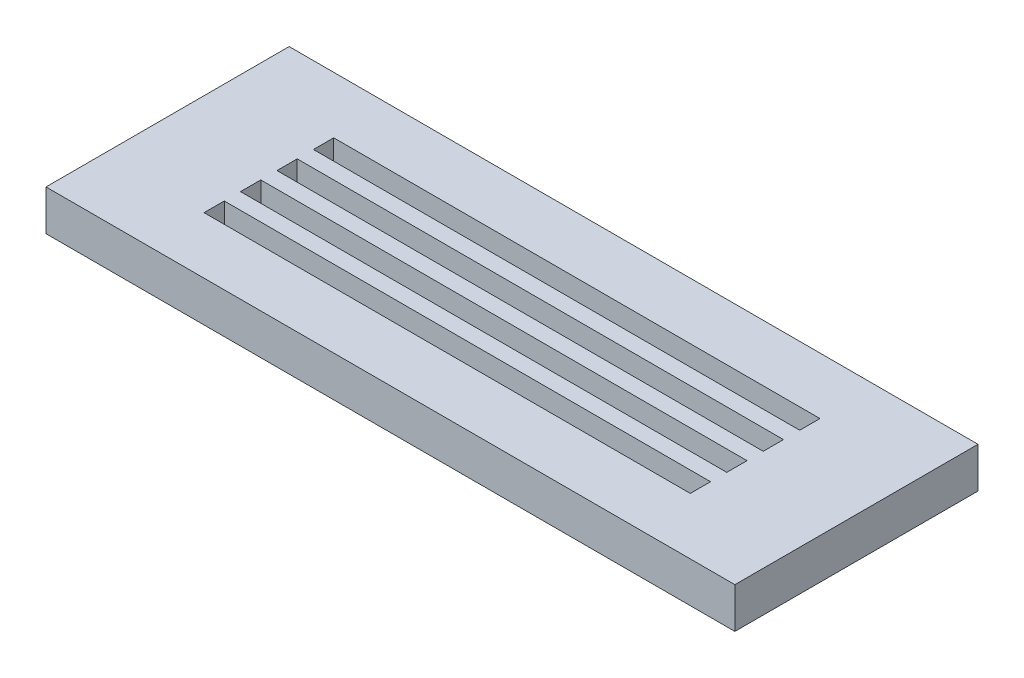
SolidWorks part; units mm, degrees
ref_plane "前视基准面" through (0, 0, 0) normal (0, 0, 1) x (1, 0, 0)
ref_plane "上视基准面" through (0, 0, 0) normal (0, 1, 0) x (1, 0, 0)
ref_plane "右视基准面" through (0, 0, 0) normal (1, 0, 0) x (0, 0, -1)
sketch "Sketch1" plane through (0, 0, 0) normal (0, 1, 0) x (1, 0, 0)
  line L1 (0, 0) -> (85, 0)
  line L2 (0, 0) -> (0, 30)
  line L3 (0, 30) -> (85, 30)
  line L4 (85, 0) -> (85, 30)
  dimension "D1" = 85
  dimension "D2" = 30
extrude "Boss-Extrude1" add sketch "Sketch1" along normal blind 5
sketch "Sketch2" plane through (0, 5, 0) normal (0, 1, 0) x (1, 0, 0)
  line L0 (85, 30) -> (0, 30) construction
  line L1 (12.5, 23) -> (72.5, 23)
  line L2 (12.5, 23) -> (12.5, 20.5)
  line L3 (12.5, 20.5) -> (72.5, 20.5)
  line L4 (72.5, 23) -> (72.5, 20.5)
  line L5 (0, 30) -> (0, 0) construction
  line L18 (12.5, 18.5) -> (72.5, 18.5)
  line L19 (12.5, 18.5) -> (12.5, 16)
  line L20 (12.5, 16) -> (72.5, 16)
  line L21 (72.5, 18.5) -> (72.5, 16)
  line L22 (12.5, 14) -> (72.5, 14)
  line L23 (12.5, 14) -> (12.5, 11.5)
  line L24 (12.5, 11.5) -> (72.5, 11.5)
  line L25 (72.5, 14) -> (72.5, 11.5)
  line L26 (12.5, 9.5) -> (72.5, 9.5)
  line L27 (12.5, 9.5) -> (12.5, 7)
  line L28 (12.5, 7) -> (72.5, 7)
  line L29 (72.5, 9.5) -> (72.5, 7)
  dimension "D1" = 7
  dimension "D2" = 2.5
  dimension "D3" = 4
  dimension "D9" = 12.5
  dimension "D10" = 60
extrude "Cut-Extrude1" cut sketch "Sketch2" against normal blind 5
